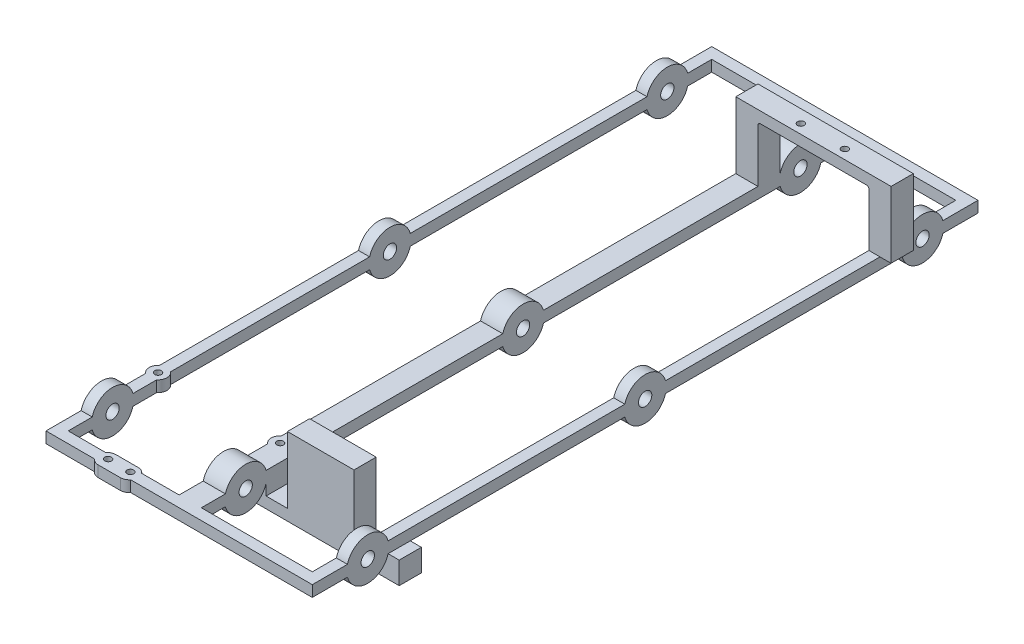
SolidWorks part; units mm, degrees
ref_plane "Front Plane" through (0, 0, 0) normal (0, 0, 1) x (1, 0, 0)
ref_plane "Top Plane" through (0, 0, 0) normal (0, 1, 0) x (1, 0, 0)
ref_plane "Right Plane" through (0, 0, 0) normal (1, 0, 0) x (0, 0, -1)
sketch "Sketch2" plane through (0, 0, 0) normal (1, 0, 0) x (0, 0, -1)
  line L0 (159.1652, 5) -> (265.8348, 5)
  line L1 (0, 0) -> (15.8348, 0)
  line L2 (0, 0) -> (0, 5)
  line L3 (0, 5) -> (15.8348, 5)
  line L4 (300, 0) -> (300, 5)
  line L5 (159.1652, 0) -> (265.8348, 0)
  line L6 (284.1652, 5) -> (300, 5)
  line L7 (284.1652, 0) -> (300, 0)
  line L8 (34.1652, 5) -> (140.8348, 5)
  line L9 (34.1652, 0) -> (140.8348, 0)
  arc A0 (159.1652, 5) -> (140.8348, 5) centre (150, 2.5) ccw
  circle A1 centre (150, 2.5) radius 3
  arc A2 (140.8348, 0) -> (159.1652, 0) centre (150, 2.5) ccw
  arc A3 (265.8348, 0) -> (284.1652, 0) centre (275, 2.5) ccw
  circle A4 centre (275, 2.5) radius 3
  arc A5 (284.1652, 5) -> (265.8348, 5) centre (275, 2.5) ccw
  arc A6 (34.1652, 5) -> (15.8348, 5) centre (25, 2.5) ccw
  circle A7 centre (25, 2.5) radius 3
  arc A8 (15.8348, 0) -> (34.1652, 0) centre (25, 2.5) ccw
  dimension "D3" = 19
  dimension "D4" = 6
  dimension "D6" = 19
  dimension "D7" = 6
  dimension "D8" = 19
  dimension "D9" = 6
  dimension "D1" = 300
  dimension "D2" = 5
  dimension "D5" = 25
  dimension "D10" = 25
extrude "Boss-Extrude1" add sketch "Sketch2" along normal blind 180
sketch "Sketch3" plane through (0, 5, 0) normal (0, 1, 0) x (1, 0, 0)
  line L0 (180, 300) -> (0, 300) construction
  line L1 (175, 295) -> (125, 295)
  line L2 (175, 295) -> (175, 5)
  line L3 (175, 5) -> (125, 5)
  line L4 (125, 295) -> (125, 5)
  line L5 (180, 159.1652) -> (180, 265.8348) construction
  line L6 (180, 0) -> (0, 0) construction
  line L7 (115, 295) -> (115, 5)
  line L8 (115, 295) -> (65, 295)
  line L9 (65, 295) -> (65, 5)
  line L10 (115, 5) -> (65, 5)
  line L11 (55, 295) -> (55, 5)
  line L12 (55, 295) -> (5, 295)
  line L13 (5, 295) -> (5, 5)
  line L14 (55, 5) -> (5, 5)
  dimension "D1" = 5
  dimension "D2" = 5
  dimension "D3" = 5
  dimension "D4" = 50
  dimension "D5" = 3
extrude "Cut-Extrude1" cut sketch "Sketch3" against normal through all both and the other way through all
sketch "Sketch4" plane through (0, 5, 0) normal (0, 1, 0) x (1, 0, 0)
  line L0 (65, 159.1652) -> (65, 265.8348) construction
  line L1 (60, 322.5694) -> (-42.0177, 322.5694)
  line L2 (60, 322.5694) -> (60, -58.4388)
  line L3 (60, -58.4388) -> (-42.0177, -58.4388)
  line L4 (-42.0177, 322.5694) -> (-42.0177, -58.4388)
  dimension "D1" = 5
extrude "Cut-Extrude2" cut sketch "Sketch4" against normal through all both and the other way through all
sketch "Sketch5" plane through (0, 0, 0) normal (0, -1, 0) x (1, 0, 0)
  line L0 (125, -140.8348) -> (125, -34.1652) construction
  line L1 (115, -34.1652) -> (125, -34.1652)
  line L2 (115, -34.1652) -> (115, -44.1652)
  line L3 (115, -44.1652) -> (125, -44.1652)
  line L4 (125, -34.1652) -> (125, -44.1652)
  line L5 (150, -5) -> (150, -25.3766)
  line L6 (125, -5) -> (175, -5) construction
  line L7 (185, -44.1652) -> (175, -44.1652)
  line L8 (175, -34.1652) -> (175, -44.1652)
  line L9 (185, -34.1652) -> (175, -34.1652)
  line L10 (185, -34.1652) -> (185, -44.1652)
  line M7 (125, -140.8348) -> (125, -34.1652)
  line M8 (125, -34.1652) -> (115, -34.1652)
  line M9 (115, -34.1652) -> (115, -140.8348)
  dimension "D1" = 10
extrude "Boss-Extrude2" add sketch "Sketch5" along normal blind 10 contours L3 M9 M7 M8 | L7 L8 L9 L10
sketch "Sketch6" plane through (125, 0, 0) normal (1, 0, 0) x (0, 0, -1)
  line L0 (44.1652, -10) -> (44.1652, 0) construction
  line L1 (34.1652, -10) -> (44.1652, -10)
  line L2 (34.1652, -10) -> (34.1652, -5)
  line L3 (34.1652, -5) -> (44.1652, -5)
  line L4 (44.1652, -10) -> (44.1652, -5)
extrude "Boss-Extrude3" add sketch "Sketch6" along normal up to next
sketch "Sketch7" plane through (0, 5, 0) normal (0, 1, 0) x (1, 0, 0)
  line L0 (125, 159.1652) -> (125, 265.8348) construction
  line L1 (115, 265.8348) -> (125, 265.8348)
  line L2 (115, 265.8348) -> (115, 255.8348)
  line L3 (115, 255.8348) -> (125, 255.8348)
  line L4 (125, 265.8348) -> (125, 255.8348)
  line L5 (150, 295) -> (150, 283.0981)
  line L6 (125, 295) -> (175, 295) construction
  line L7 (185, 255.8348) -> (175, 255.8348)
  line L8 (175, 265.8348) -> (175, 255.8348)
  line L9 (185, 265.8348) -> (175, 265.8348)
  line L10 (185, 265.8348) -> (185, 255.8348)
  line M7 (125, 159.1652) -> (125, 265.8348)
  line M8 (125, 265.8348) -> (115, 265.8348)
  line M9 (115, 265.8348) -> (115, 159.1652)
  dimension "D1" = 10
extrude "Boss-Extrude4" add sketch "Sketch7" along normal blind 30 contours L3 M9 M7 M8 | L10 L9 L8 L7
sketch "Sketch8" plane through (125, 0, 0) normal (1, 0, 0) x (0, 0, -1)
  line L0 (255.8348, 35) -> (255.8348, 5) construction
  line L1 (265.8348, 35) -> (255.8348, 35)
  line L2 (265.8348, 35) -> (265.8348, 30)
  line L3 (265.8348, 30) -> (255.8348, 30)
  line L4 (255.8348, 35) -> (255.8348, 30)
  dimension "D1" = 5
extrude "Boss-Extrude5" add sketch "Sketch8" along normal up to next
sketch "Sketch9" plane through (0, -5, 0) normal (0, 1, 0) x (1, 0, 0)
  line L0 (175, 44.1652) -> (125, 44.1652) construction
  line L1 (164.6267, 34.1652) -> (134.6267, 34.1652)
  line L2 (164.6267, 34.1652) -> (164.6267, 44.1652)
  line L3 (164.6267, 44.1652) -> (134.6267, 44.1652)
  line L4 (134.6267, 34.1652) -> (134.6267, 44.1652)
  line L5 (164.6267, 34.1652) -> (134.6267, 44.1652) construction
  line L6 (164.6267, 44.1652) -> (134.6267, 34.1652) construction
  point P0 (149.6267, 39.1652)
  dimension "D1" = 30
extrude "Boss-Extrude6" add sketch "Sketch9" along normal blind 30
fillet "Fillet1" radius 1 2 edges at (125, 30, -260.8348) (175, 30, -260.8348)
sketch "Sketch10" plane through (0, 30, 0) normal (0, -1, 0) x (1, 0, 0)
  circle A0 centre (159.9603, -260.0252) radius 1.5
  circle A1 centre (140.127, -260.0252) radius 1.5
extrude "Cut-Extrude3" cut sketch "Sketch10" against normal up to next
sketch "Sketch12" plane through (0, 0, 0) normal (0, -1, 0) x (-1, 0, 0)
  line L0 (-60, 34.1652) -> (-60, 140.8348) construction
  line L1 (-180, 0) -> (-60, 0) construction
  line L2 (-85, 2.5) -> (-95, 2.5) construction
  line L3 (-85, -1.5) -> (-95, -1.5)
  line L4 (-85, 6.5) -> (-95, 6.5)
  line L5 (-65, 15.8348) -> (-65, 5) construction
  line L7 (-115, 44.1652) -> (-115, 140.8348) construction
  circle A0 centre (-62.5, 48) radius 4
  arc A1 (-85, -1.5) -> (-85, 6.5) centre (-85, 2.5) ccw
  arc A2 (-95, 6.5) -> (-95, -1.5) centre (-95, 2.5) ccw
  circle A3 centre (-117.5, 48) radius 4
  point P8 (-90, 2.5)
  dimension "D2" = 8
  dimension "D6" = 4
  dimension "D8" = 2.5
  dimension "D9" = 8
  dimension "D1" = 2.5
  dimension "D3" = 48
  dimension "D4" = 10
  dimension "D5" = 20
  dimension "D7" = 2.5
extrude "Boss-Extrude7" add sketch "Sketch12" against normal blind 5
sketch "Sketch13" plane through (0, 0, 0) normal (0, -1, 0) x (-1, 0, 0)
  line L0 (-65, 44.8775) -> (-65, 34.1652) construction
  line L3 (-81.8775, 0) -> (-60, 0) construction
  line L4 (-180, 0) -> (-98.1225, 0) construction
  line L6 (-115, 44.1652) -> (-115, 44.8775) construction
  line L7 (-115, 5) -> (-115, 15.8348) construction
  circle A0 centre (-62.5, 48) radius 1.5
  circle A1 centre (-85, 3) radius 1.5
  circle A2 centre (-95, 3) radius 1.5
  circle A3 centre (-117.5, 48) radius 1.5
  dimension "D1" = 3
  dimension "D5" = 3
  dimension "D7" = 3
  dimension "D8" = 3
  dimension "D2" = 2.5
  dimension "D3" = 48
  dimension "D4" = 48
  dimension "D6" = 2.5
  dimension "D9" = 10
  dimension "D10" = 20
  dimension "D11" = 3
extrude "Cut-Extrude4" cut sketch "Sketch13" against normal through all
